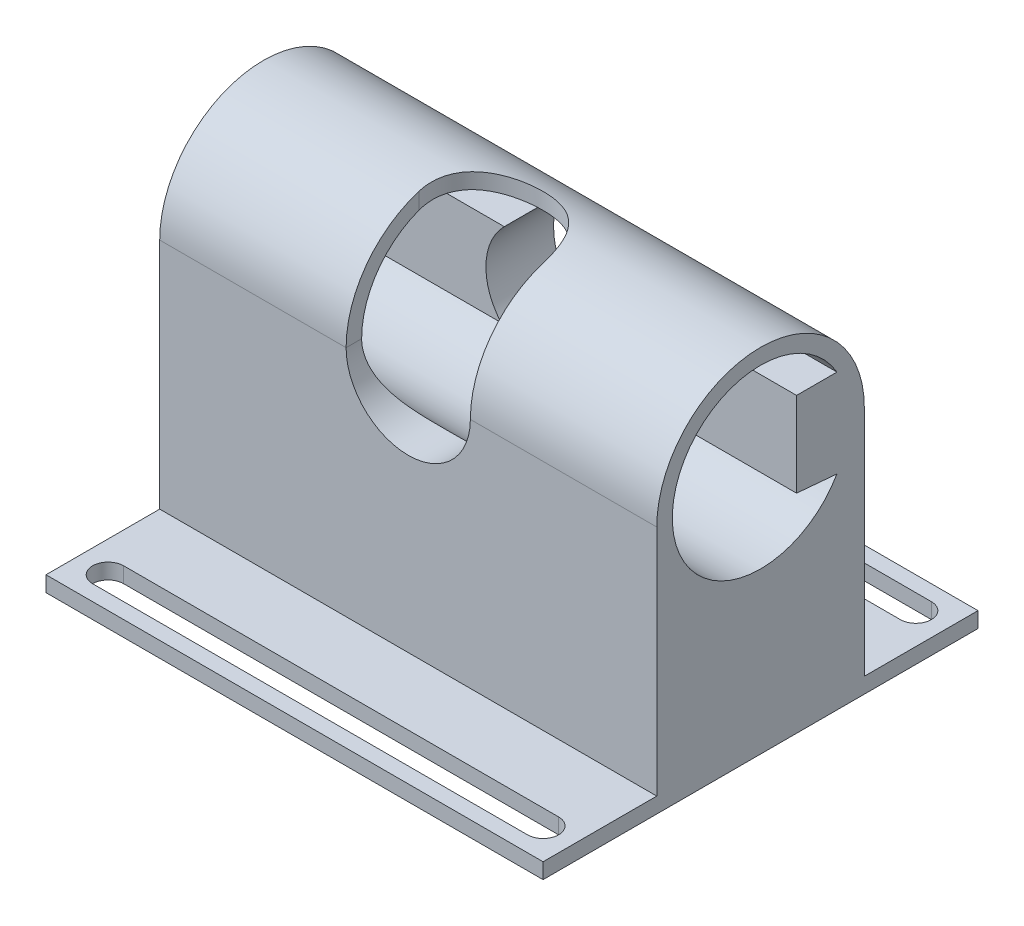
SolidWorks part; units mm, degrees
ref_plane "Front Plane" through (0, 0, 0) normal (0, 0, 1) x (1, 0, 0)
ref_plane "Top Plane" through (0, 0, 0) normal (0, 1, 0) x (1, 0, 0)
ref_plane "Right Plane" through (0, 0, 0) normal (1, 0, 0) x (0, 0, -1)
sketch "Sketch1" plane through (0, 0, 0) normal (1, 0, 0) x (0, 0, -1)
  line L0 (15.6179, -9.017) -> (7.366, -8.2951)
  line L1 (7.366, -9.017) -> (15.6179, -9.017) construction
  line L2 (7.366, -9.017) -> (7.366, 9.017) construction
  line L3 (7.366, 9.017) -> (15.6179, 9.017)
  line L4 (7.366, 9.017) -> (7.366, -8.2951)
  arc A0 (15.6179, 9.017) -> (15.6179, -9.017) centre (0, 0) ccw
  circle A1 centre (0, 0) radius 21.209
  point P8 (-18.034, 0)
  point P9 (7.366, 0)
  dimension "D1" = 36.068
  dimension "D2" = 3.175
  dimension "D3" = 25.4
  dimension "D4" = 18.034
  dimension "D5" = 5
extrude "Boss-Extrude1" add sketch "Sketch1" along normal mid plane 101.6
sketch "Sketch3" plane through (0, 0, 0) normal (0, 1, 0) x (1, 0, 0)
  line L0 (-12.7, -6.35) -> (-12.7, -32.197)
  line L1 (-12.7, -32.197) -> (12.7, -32.197)
  line L2 (12.7, -32.197) -> (12.7, -6.35)
  arc A0 (12.7, -6.35) -> (-12.7, -6.35) centre (0, -6.35) ccw
  dimension "D1" = 25.4
  dimension "D2" = 6.35
extrude "Cut-Extrude2" cut sketch "Sketch3" along normal through all
sketch "Sketch4" plane through (0, 0, 0) normal (0, 1, 0) x (1, 0, 0)
  line L1 (50.8, -21.209) -> (-50.8, -21.209)
  line L2 (50.8, -21.209) -> (50.8, 21.209)
  line L3 (50.8, 21.209) -> (-50.8, 21.209)
  line L4 (-50.8, -21.209) -> (-50.8, 21.209)
extrude "Boss-Extrude3" add sketch "Sketch4" along normal up to surface (50.8 mm away) from offset 50.8 up to face at (-50.8, 0, -21.209) offset against normal yes
sketch "Sketch2" plane through (0, 0, 0) normal (0, 0, 1) x (1, 0, 0)
  circle A0 centre (0, 0) radius 12.7
  dimension "D1" = 25.4
extrude "Cut-Extrude1" cut sketch "Sketch2" against normal through all both and the other way through all
sketch "Sketch5" plane through (0, -50.8, 0) normal (0, -1, 0) x (1, 0, 0)
  line L0 (50.8, 21.209) -> (50.8, -21.209) construction
  line L1 (50.8, 44.45) -> (-50.8, 44.45)
  line L2 (50.8, 44.45) -> (50.8, -44.45)
  line L3 (50.8, -44.45) -> (-50.8, -44.45)
  line L4 (-50.8, 44.45) -> (-50.8, -44.45)
  line L5 (-50.8, -21.209) -> (-50.8, 21.209) construction
  line L6 (44.45, 41.275) -> (-44.45, 41.275)
  line L7 (44.45, 34.925) -> (-44.45, 34.925)
  line L8 (50.8, 0) -> (-50.8, 0) construction
  line L9 (44.45, -41.275) -> (-44.45, -41.275)
  line L10 (44.45, -34.925) -> (-44.45, -34.925)
  arc A0 (44.45, 34.925) -> (44.45, 41.275) centre (44.45, 38.1) ccw
  arc A1 (-44.45, 41.275) -> (-44.45, 34.925) centre (-44.45, 38.1) ccw
  arc A2 (44.45, -34.925) -> (44.45, -41.275) centre (44.45, -38.1) cw
  arc A3 (-44.45, -41.275) -> (-44.45, -34.925) centre (-44.45, -38.1) cw
  point P9 (47.625, 38.1)
  point P15 (-47.625, 38.1)
  point P18 (50.8, 51.6877)
  point P19 (0, 0)
  dimension "D1" = 6.35
  dimension "D2" = 3.175
  dimension "D4" = 3.175
  dimension "D3" = 3.175
  dimension "D5" = 38.1
extrude "Boss-Extrude4" add sketch "Sketch5" against normal blind 3.175
